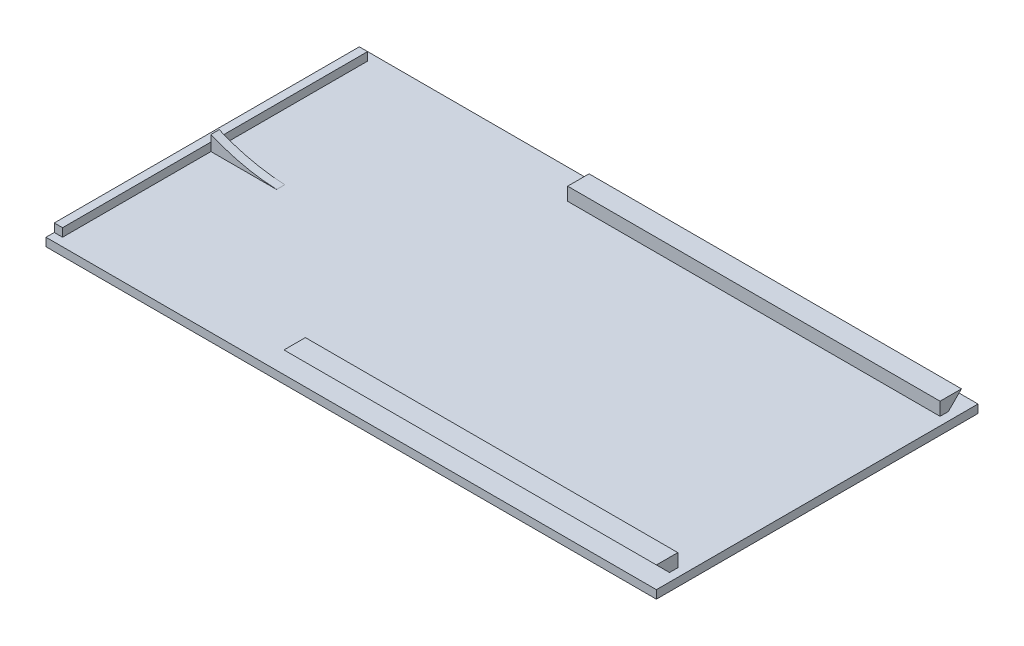
SolidWorks part; units mm, degrees
ref_plane "Plano frontal" through (0, 0, 0) normal (0, 0, 1) x (1, 0, 0)
ref_plane "Plano superior" through (0, 0, 0) normal (0, 1, 0) x (1, 0, 0)
ref_plane "Plano direito" through (0, 0, 0) normal (1, 0, 0) x (0, 0, -1)
sketch "Esboço1" plane through (0, 0, 0) normal (0, 1, 0) x (1, 0, 0)
  line L1 (0, 0) -> (93, 0)
  line L2 (0, 0) -> (0, 49)
  line L3 (0, 49) -> (93, 49)
  line L4 (93, 0) -> (93, 49)
  dimension "D1" = 93
  dimension "D2" = 49
extrude "Ressalto-extrusão1" add sketch "Esboço1" along normal blind 1.26
sketch "Esboço2" plane through (0, 1.26, 0) normal (0, 1, 0) x (1, 0, 0)
  line L0 (0, 49) -> (0, 0) construction
  line L1 (0, 47.74) -> (1.26, 47.74)
  line L2 (0, 47.74) -> (0, 1.26)
  line L3 (0, 1.26) -> (1.26, 1.26)
  line L4 (1.26, 47.74) -> (1.26, 1.26)
  line L5 (93, 49) -> (0, 49) construction
  line L6 (0, 0) -> (93, 0) construction
  dimension "D1" = 1.26
  dimension "D2" = 1.26
  dimension "D3" = 1.26
extrude "Ressalto-extrusão2" add sketch "Esboço2" along normal blind 1.26
sketch "Esboço3" plane through (0, 1.26, 0) normal (0, 1, 0) x (1, 0, 0)
  line L0 (1.26, 1.26) -> (1.26, 47.74) construction
  line L1 (93, 49) -> (0, 49) construction
  line L2 (1.26, 25.13) -> (11.26, 25.13)
  line L3 (1.26, 25.13) -> (1.26, 23.87)
  line L4 (1.26, 23.87) -> (11.26, 23.87)
  line L5 (11.26, 25.13) -> (11.26, 23.87)
  dimension "D1" = 1.26
  dimension "D2" = 10
  dimension "D3" = 23.87
extrude "Ressalto-extrusão3" add sketch "Esboço3" along normal blind 2.26
sketch "Esboço4" plane through (0, 0, -23.87) normal (0, 0, 1) x (1, 0, 0)
  line L0 (1.26, 3.52) -> (11.26, 3.52) construction
  line L1 (1.26, 3.52) -> (11.26, 3.52)
  line L2 (11.26, 3.52) -> (11.26, 1.26)
  arc A0 (1.26, 3.52) -> (11.26, 1.26) centre (12.4759, 29.8941) ccw
  dimension "D1" = 26.3741
extrude "Corte-extrusão1" cut sketch "Esboço4" against normal blind 1.26
sketch "Esboço5" plane through (0, 1.26, 0) normal (0, 1, 0) x (1, 0, 0)
  line L0 (93, 0) -> (93, 49) construction
  line L1 (0, 0) -> (93, 0) construction
  line L2 (35, 1.26) -> (91.74, 1.26)
  line L3 (35, 44.48) -> (91.74, 44.48)
  line L4 (35, 44.48) -> (35, 47.74)
  line L5 (35, 47.74) -> (91.74, 47.74)
  line L6 (91.74, 44.48) -> (91.74, 47.74)
  line L7 (35, 1.26) -> (35, 4.52)
  line L8 (35, 4.52) -> (91.74, 4.52)
  line L9 (91.74, 1.26) -> (91.74, 4.52)
  line L10 (93, 49) -> (0, 49) construction
  dimension "D1" = 1.26
  dimension "D2" = 1.26
  dimension "D3" = 1.26
  dimension "D4" = 1.26
  dimension "D5" = 3.26
  dimension "D6" = 3.26
  dimension "D7" = 56.74
  dimension "D8" = 56.74
extrude "Ressalto-extrusão4" add sketch "Esboço5" along normal blind 2
sketch "Esboço6" plane through (91.74, 0, 0) normal (1, 0, 0) x (0, 0, -1)
  line L0 (3.2622, 1.26) -> (1.26, 3.26)
  line L1 (1.26, 1.26) -> (4.52, 1.26) construction
  line L2 (1.26, 3.26) -> (1.26, 1.26)
  line L3 (1.26, 1.26) -> (3.2622, 1.26)
  line L4 (45.7378, 1.26) -> (47.74, 3.26)
  line L6 (44.48, 1.26) -> (47.74, 1.26) construction
  line L9 (47.74, 3.26) -> (47.74, 1.26)
  line L10 (47.74, 1.26) -> (45.7378, 1.26)
  dimension "D1" = 2.83
  dimension "D2" = 2.83
extrude "Corte-extrusão3" cut sketch "Esboço6" against normal blind 62
